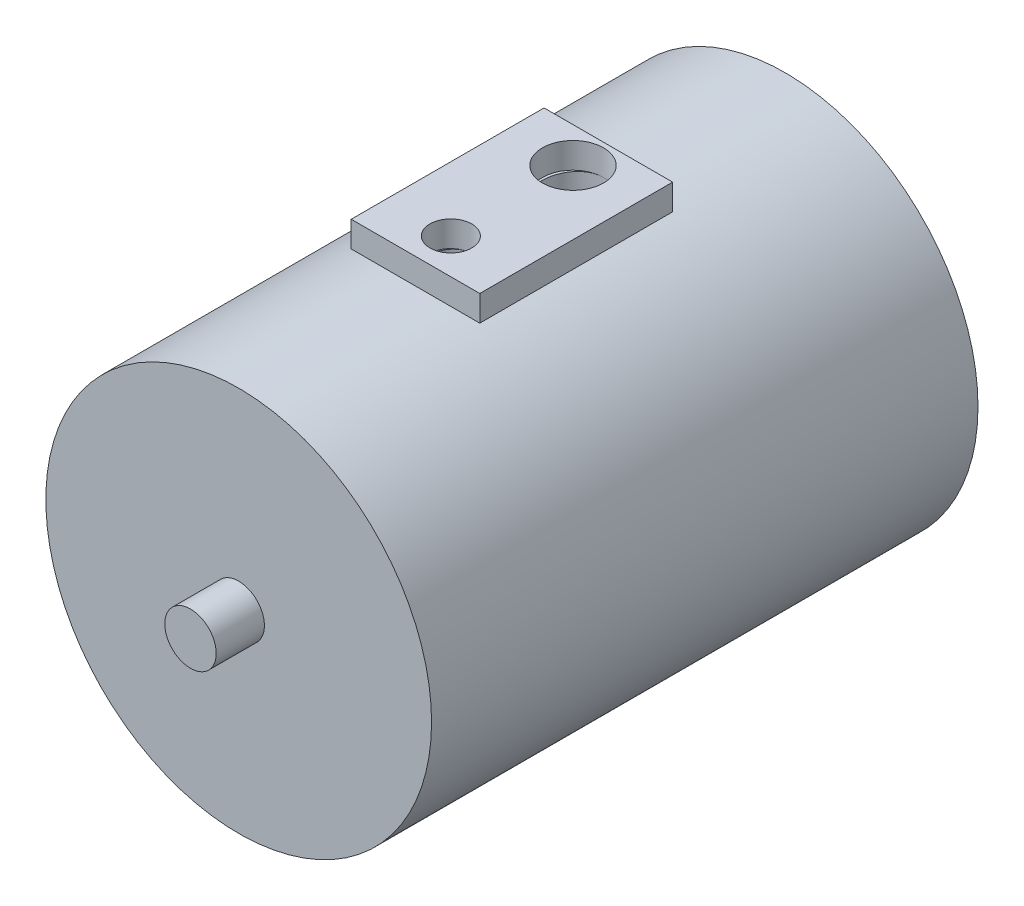
SolidWorks part; units mm, degrees
ref_plane "Front Plane" through (0, 0, 0) normal (0, 0, 1) x (1, 0, 0)
ref_plane "Top Plane" through (0, 0, 0) normal (0, 1, 0) x (1, 0, 0)
ref_plane "Right Plane" through (0, 0, 0) normal (1, 0, 0) x (0, 0, -1)
sketch "Sketch1" plane through (0, 0, 0) normal (0, 0, 1) x (1, 0, 0)
  line L0 (0, 113.2576) -> (0, -119.697) construction
  line L1 (-149.6212, 0) -> (177.6515, 0) construction
  circle A0 centre (0, 0) radius 60
  dimension "D1" = 120
extrude "Boss-Extrude2" add sketch "Sketch1" along normal mid plane 170
sketch "Sketch2" plane through (0, 0, 0) normal (0, 0, 1) x (1, 0, 0)
  line L0 (-20, 68) -> (20, 68)
  line L1 (-20, 68) -> (-20, 60)
  line L2 (-20, 60) -> (20, 60)
  line L3 (20, 68) -> (20, 60)
  line L4 (-20, 68) -> (20, 60) construction
  line L5 (-20, 60) -> (20, 68) construction
  line L6 (-96.5154, 0) -> (128.5735, 0) construction
  line L7 (0, -91.2633) -> (0, 105.9964) construction
  circle A0 centre (0, 0) radius 60 construction
  point P0 (0, 64)
  dimension "D1" = 8
  dimension "D2" = 40
extrude "Boss-Extrude3" add sketch "Sketch2" along normal mid plane 60 separate body
sketch "Sketch3" plane through (0, 0, 85) normal (0, 0, 1) x (1, 0, 0)
  circle A0 centre (0, 0) radius 8
  dimension "D1" = 16
extrude "Boss-Extrude4" add sketch "Sketch3" along normal mid plane 30
sketch "Sketch5" plane through (0, 68, 0) normal (0, 1, 0) x (1, 0, 0)
  line L0 (0, 69.3278) -> (0, -78.496) construction
  line L1 (-45.1332, 0) -> (48.683, 0) construction
  line L2 (20, 30) -> (-20, 30) construction
  circle A0 centre (0, -19) radius 6.5
  circle A1 centre (0, 19) radius 9.5
  dimension "D3" = 19
  dimension "D4" = 13
  dimension "D1" = 38
  dimension "D2" = 11
extrude "Cut-Extrude1" cut sketch "Sketch5" against normal blind 25 contours A1 | A0
